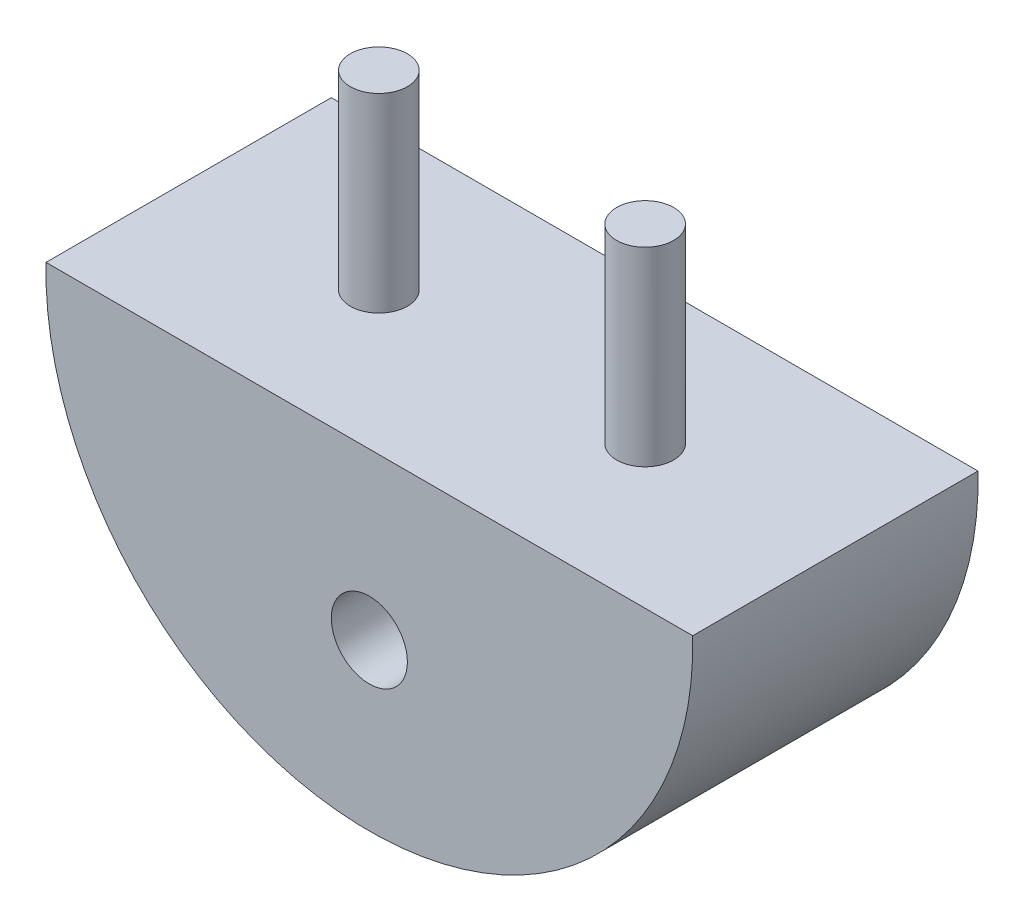
SolidWorks part; units mm, degrees
ref_plane "Front Plane" through (0, 0, 0) normal (0, 0, 1) x (1, 0, 0)
ref_plane "Top Plane" through (0, 0, 0) normal (0, 1, 0) x (1, 0, 0)
ref_plane "Right Plane" through (0, 0, 0) normal (1, 0, 0) x (0, 0, -1)
sketch "Sketch1" plane through (0, 0, 0) normal (0, 0, 1) x (1, 0, 0)
  line L0 (-16.3311, 6.3182) -> (17.6689, 6.3182)
  line L1 (0.6689, -11.0771) -> (0.6689, 6.3182) construction
  arc A0 (-16.3311, 6.3182) -> (17.6689, 6.3182) centre (0.6689, 5.9274) ccw
  circle A1 centre (0.6689, -2.3794) radius 2
  dimension "D2" = 4
  dimension "D1" = 34
extrude "Boss-Extrude1" add sketch "Sketch1" along normal blind 15
sketch "Sketch2" plane through (0, 6.3182, 0) normal (0, 1, 0) x (1, 0, 0)
  line L0 (-16.3311, -15) -> (-16.3311, 0) construction
  line L1 (17.6689, -15) -> (17.6689, 0) construction
  circle A0 centre (-6.3311, -7.5) radius 1.5
  circle A1 centre (7.6689, -7.5) radius 1.5
  dimension "D1" = 3
  dimension "D2" = 3
  dimension "D3" = 10
  dimension "D4" = 10
extrude "Boss-Extrude2" add sketch "Sketch2" along normal blind 10
